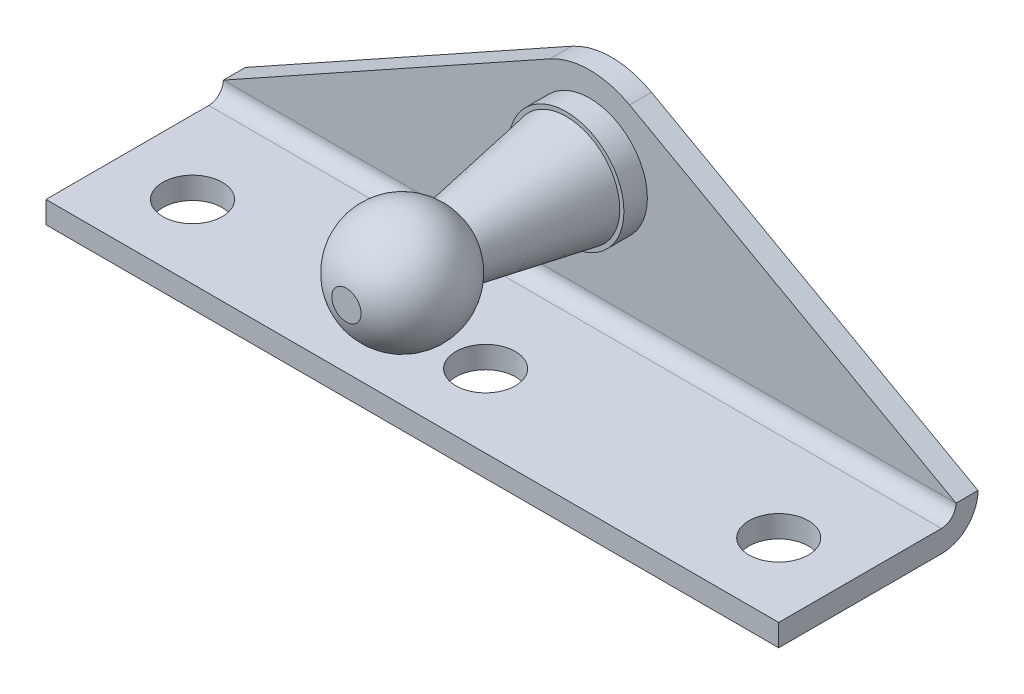
SolidWorks part; units mm, degrees
ref_plane "Front" through (0, 0, 0) normal (0, 0, 1) x (1, 0, 0)
ref_plane "Top" through (0, 0, 0) normal (0, 1, 0) x (1, 0, 0)
ref_plane "Right" through (0, 0, 0) normal (1, 0, 0) x (0, 0, -1)
sketch "Sketch1" plane through (0, 0, 0) normal (0, 0, 1) x (1, 0, 0)
  line L0 (-31.75, -12.7) -> (31.75, -12.7)
  line L1 (31.75, -12.7) -> (31.75, -9.525)
  line L2 (31.75, -9.525) -> (3.4576, 6.215)
  line L3 (-3.4576, 6.215) -> (-31.75, -9.525)
  line L4 (-31.75, -9.525) -> (-31.75, -12.7)
  line L5 (0, 0) -> (0, -12.7) construction
  line L6 (-31.75, -9.525) -> (31.75, -9.525) construction
  arc A0 (3.4576, 6.215) -> (-3.4576, 6.215) centre (0, 0) ccw
  dimension "D3" = 12.7
  dimension "D1" = 3.175
  dimension "D2" = 63.5
  dimension "D4" = 19.812
extrude "Extrude1" add sketch "Sketch1" along normal blind 1.905
sketch "Sketch4" plane through (0, -12.7, 0) normal (0, -1, 0) x (1, 0, 0)
  line L0 (31.75, 1.905) -> (31.75, 0) construction
  line L1 (-31.75, 17.272) -> (31.75, 17.272)
  line L2 (-31.75, 17.272) -> (-31.75, 0)
  line L3 (-31.75, 0) -> (31.75, 0)
  line L4 (31.75, 17.272) -> (31.75, 0)
  line L5 (-31.75, 0) -> (31.75, 0) construction
  line L6 (-31.75, 1.905) -> (-31.75, 0) construction
  dimension "D1" = 17.272
extrude "Extrude2" add sketch "Sketch4" against normal blind 1.905
fillet "Fillet1" radius 1.27 1 edges at (0, -10.795, 1.905)
fillet "Fillet2" radius 3.175 1 edges at (0, -12.7, 0)
sketch "Sketch5" plane through (0, -12.7, 0) normal (0, -1, 0) x (1, 0, 0)
  line L1 (0, 0) -> (0, 10.922) construction
  line L2 (-25.4, 10.922) -> (25.4, 10.922) construction
  line L3 (31.75, 17.272) -> (-31.75, 17.272) construction
  circle A0 centre (-25.4, 10.922) radius 2.5781
  circle A1 centre (25.4, 10.922) radius 2.5781
  circle A2 centre (0, 10.922) radius 2.5781
  dimension "D1" = 6.35
  dimension "D3" = 50.8
  dimension "D4" = 5.1562
extrude "Cut-Extrude1" cut sketch "Sketch5" against normal through all
ref_plane "Plane1" through (0, 0, 0) normal (0, -1, 0) x (1, 0, 0)
sketch "Sketch3" plane through (0, 0, 0) normal (0, -1, 0) x (1, 0, 0)
  line L0 (0, 1.905) -> (0, 22.987)
  line L1 (0, 22.987) -> (1.27, 22.987)
  line L2 (2.8522, 14.0443) -> (4.6405, 3.937)
  line L3 (4.6405, 3.937) -> (5, 3.937)
  line L4 (5, 3.937) -> (5, 1.905)
  line L5 (5, 1.905) -> (0, 1.905)
  line L6 (0, 1.905) -> (0, -3.095) construction
  line L7 (-31.75, 1.905) -> (31.75, 1.905) construction
  arc A0 (1.27, 22.987) -> (2.8522, 14.0443) centre (0, 18.151) cw
  dimension "D1" = 5
  dimension "D2" = 21.082
  dimension "D3" = 2.032
  dimension "D4" = 1.27
revolve "Revolve1" add sketch "Sketch3" angle 360 about L6
